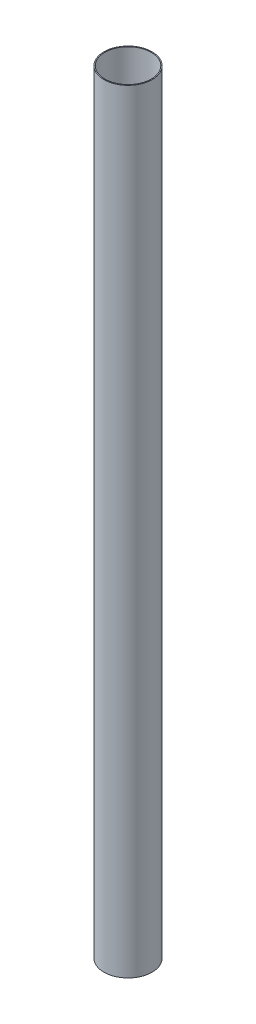
SolidWorks part; units mm, degrees
material "Wildman Fiberglass"
ref_plane "Front Plane" through (0, 0, 0) normal (0, 0, 1) x (1, 0, 0)
ref_plane "Top Plane" through (0, 0, 0) normal (0, 1, 0) x (1, 0, 0)
ref_plane "Right Plane" through (0, 0, 0) normal (1, 0, 0) x (0, 0, -1)
sketch "Sketch1" plane through (0, 0, 0) normal (0, 1, 0) x (1, 0, 0)
  circle A0 centre (0, 0) radius 38.1
  circle A1 centre (0, 0) radius 39.624
  dimension "D1" = 79.248
  dimension "D2" = 76.2
extrude "Boss-Extrude1" add sketch "Sketch1" along normal blind 1270
equation "\"Length\"= 50"
equation "\"D1@Boss-Extrude1\"=\"Length\""
